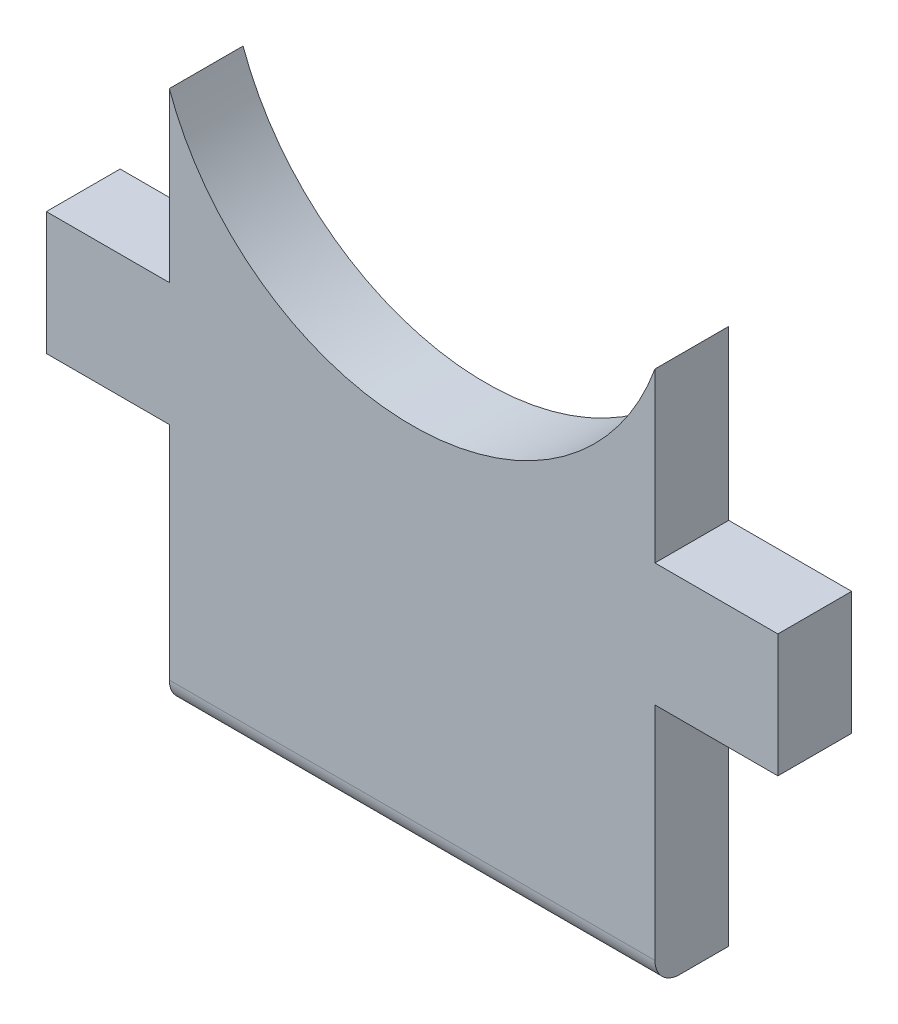
SolidWorks part; units mm, degrees
material "PLA"
ref_plane "Alzado" through (0, 0, 0) normal (0, 0, 1) x (1, 0, 0)
ref_plane "Planta" through (0, 0, 0) normal (0, 1, 0) x (1, 0, 0)
ref_plane "Vista lateral" through (0, 0, 0) normal (1, 0, 0) x (0, 0, -1)
sketch "Croquis1" plane through (0, 0, 0) normal (0, 0, 1) x (1, 0, 0)
  line L0 (-9.875, 0) -> (-9.875, -25.4)
  line L1 (-9.875, -25.4) -> (9.875, -25.4)
  line L2 (9.875, -25.4) -> (9.875, 0)
  line L4 (-9.875, -10.4) -> (-14.875, -10.4)
  line L5 (-9.875, -10.4) -> (-9.875, -15.4)
  line L6 (-9.875, -15.4) -> (-14.875, -15.4)
  line L7 (-14.875, -10.4) -> (-14.875, -15.4)
  line L8 (9.875, -10.4) -> (14.875, -10.4)
  line L9 (9.875, -10.4) -> (9.875, -15.4)
  line L10 (9.875, -15.4) -> (14.875, -15.4)
  line L11 (14.875, -10.4) -> (14.875, -15.4)
  circle A0 centre (0, 0) radius 9.875
  dimension "D1" = 19.75
  dimension "D2" = 25.4
  dimension "D3" = 5
  dimension "D4" = 5
  dimension "D5" = 5
  dimension "D6" = 5
  dimension "D7" = 10
  dimension "D8" = 10
extrude "Saliente-Extruir1" add sketch "Croquis1" along normal blind 3 contours A0 | A0 L0 L1 L2 | L11 L8 L2 L10 | L4 L7 L6 L0
fillet "Redondeo1" radius 1 1 edges at (0, -25.4, 3)
sketch "Croquis2" plane through (0, 0, 3) normal (0, 0, 1) x (1, 0, 0)
  circle A0 centre (0, 0) radius 10.5
  dimension "D1" = 21
extrude "Cortar-Extruir1" cut sketch "Croquis2" against normal blind 10
